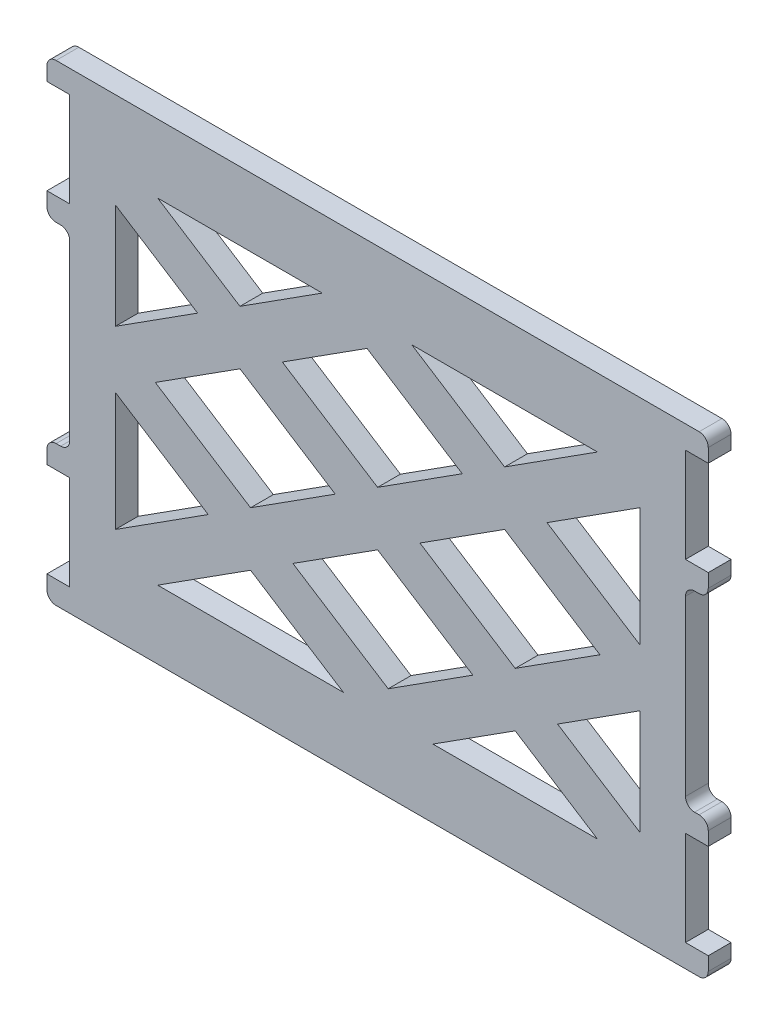
SolidWorks part; units mm, degrees
ref_plane "Front Plane" through (0, 0, 0) normal (0, 0, 1) x (1, 0, 0)
ref_plane "Top Plane" through (0, 0, 0) normal (0, 1, 0) x (1, 0, 0)
ref_plane "Right Plane" through (0, 0, 0) normal (1, 0, 0) x (0, 0, -1)
sketch "Sketch1" plane through (0, 0, 0) normal (0, 0, 1) x (1, 0, 0)
  line L1 (-44.9115, 28.3715) -> (9.0885, 28.3715)
  line L2 (-44.9115, 28.3715) -> (-44.9115, -9.0285)
  line L3 (-44.9115, -9.0285) -> (9.0885, -9.0285)
  line L4 (9.0885, 28.3715) -> (9.0885, -9.0285)
  dimension "D1" = 54
  dimension "D2" = 37.4
extrude "Boss-Extrude1" add sketch "Sketch1" along normal blind 2
sketch "Sketch2" plane through (0, 0, 2) normal (0, 0, 1) x (1, 0, 0)
  line L0 (-37.1977, 24.3715) -> (-29.9813, 19.7593)
  line L1 (-40.9115, 21.9979) -> (-33.6951, 17.3857)
  line L2 (1.3747, 24.3715) -> (-6.7702, 19.1659)
  line L3 (5.0885, 21.9979) -> (-3.0564, 16.7923)
  line L4 (-40.9115, 24.3715) -> (5.0885, -5.0285) construction
  line L5 (5.0885, 24.3715) -> (-40.9115, -5.0285) construction
  line L6 (-22.7649, 24.3715) -> (-29.9813, 19.7593)
  line L7 (-37.4089, 10.2649) -> (-18.84, 22.1329)
  line L8 (-40.9115, 24.3715) -> (-40.9115, -5.0285)
  line L9 (-40.9115, -5.0285) -> (5.0885, -5.0285)
  line L10 (5.0885, -5.0285) -> (5.0885, 24.3715)
  line L11 (5.0885, 24.3715) -> (-40.9115, 24.3715)
  line L12 (-40.9115, 21.9979) -> (-40.9115, 12.7735)
  line L13 (-37.1977, -5.0285) -> (-20.908, -5.0285)
  line L14 (5.0885, -2.6549) -> (5.0885, 6.5696)
  line L15 (1.3747, 24.3715) -> (-14.915, 24.3715)
  line L16 (-13.0581, -5.0285) -> (-5.8417, -0.4163)
  line L17 (-16.9831, -2.7898) -> (-9.5555, 1.9573)
  line L18 (-14.915, 24.3715) -> (-6.7702, 19.1659)
  line L19 (-18.84, 22.1329) -> (-10.4839, 16.7923)
  line L20 (-40.9115, 7.7564) -> (-32.7667, 2.5507)
  line L21 (-37.4089, 10.2649) -> (-29.0529, 4.9243)
  line L22 (-3.0564, 16.7923) -> (5.0885, 11.5867)
  line L23 (-6.7702, 14.4187) -> (1.5859, 9.0781)
  line L24 (-10.4839, 16.7923) -> (-17.9115, 12.0451)
  line L25 (-6.7702, 14.4187) -> (-14.1977, 9.6715)
  line L26 (-33.6951, 17.3857) -> (-40.9115, 12.7735)
  line L27 (-29.9813, 15.0121) -> (-21.6253, 9.6715)
  line L28 (-26.2675, 17.3857) -> (-17.9115, 12.0451)
  line L29 (-32.7667, 2.5507) -> (-40.9115, -2.6549)
  line L30 (-29.0529, 0.1771) -> (-37.1977, -5.0285)
  line L31 (-5.8417, 4.3309) -> (1.5859, 9.0781)
  line L32 (-2.1279, 1.9573) -> (5.0885, 6.5696)
  line L33 (-2.1279, 1.9573) -> (5.0885, -2.6549)
  line L34 (-5.8417, -0.4163) -> (1.3747, -5.0285)
  line L35 (-21.6253, 9.6715) -> (-29.0529, 4.9243)
  line L36 (-17.9115, 7.2979) -> (-9.5555, 1.9573)
  line L37 (-17.9115, 7.2979) -> (-25.3391, 2.5507)
  line L38 (-14.1977, 9.6715) -> (-5.8417, 4.3309)
  line L39 (-22.7649, 24.3715) -> (-37.1977, 24.3715)
  line L40 (5.0885, 11.5867) -> (5.0885, 21.9979)
  line L41 (-13.0581, -5.0285) -> (1.3747, -5.0285)
  line L42 (-40.9115, 7.7564) -> (-40.9115, -2.6549)
  line L43 (-25.3391, 2.5507) -> (-16.9831, -2.7898)
  line L44 (-29.0529, 0.1771) -> (-20.908, -5.0285)
  dimension "D2" = 2
  dimension "D3" = 2
  dimension "D4" = 2
  dimension "D5" = 2
  dimension "D6" = 15
  dimension "D7" = 4
  dimension "D8" = 15
  dimension "D9" = 4
  dimension "D10" = 14
  dimension "D11" = 4
  dimension "D12" = 14
  dimension "D13" = 4
  dimension "D1" = 4
extrude "Cut-Extrude1" cut sketch "Sketch2" against normal through all contours L6 L39 L0 | L26 L1 L12 | L35 L27 L7 L21 | L7 L28 L24 L19 | L15 L18 L2 | L22 L40 L3 | L25 L38 L31 L23 | L37 L43 L17 L36 | L44 L30 L13 | L20 L42 L29 | L16 L41 L34 | L32 L33 L14
ref_plane "Plane1" through (0, 9.6715, 0) normal (0, -1, 0) x (-1, 0, 0)
ref_plane "Plane2" through (-17.9115, 0, 0) normal (-1, 0, 0) x (0, 0, 1)
sketch "Sketch3" plane through (0, -9.0285, 0) normal (0, -1, 0) x (1, 0, 0)
  line L0 (9.0885, 2) -> (11.0885, 2)
  line L1 (11.0885, 2) -> (11.0885, 0)
  line L2 (11.0885, 0) -> (9.0885, 0)
  line L3 (-44.9115, 0) -> (9.0885, 0) construction
  line L4 (-44.9115, 2) -> (-46.9115, 2)
  line L5 (-46.9115, 2) -> (-46.9115, 0)
  line L6 (-46.9115, 0) -> (-44.9115, 0)
  line L7 (-44.9115, 2) -> (-44.9115, 0) construction
  line L8 (9.0885, 2) -> (9.0885, 0) construction
  line L9 (-44.9115, 2) -> (9.0885, 2)
  line L10 (9.0885, 0) -> (-44.9115, 0)
  dimension "D1" = 2
  dimension "D2" = 2
extrude "Boss-Extrude2" add sketch "Sketch3" along normal blind 2
sketch "Sketch4" plane through (9.0885, 0, 0) normal (1, 0, 0) x (0, 0, -1)
  line L0 (-2, -9.0285) -> (0, -9.0285) construction
  line L1 (-2, -0.7285) -> (0, -0.7285)
  line L2 (-2, -0.7285) -> (-2, 1.2715)
  line L3 (-2, 1.2715) -> (0, 1.2715)
  line L4 (0, -0.7285) -> (0, 1.2715)
  line L5 (-2, -9.0285) -> (-2, 28.3715) construction
  line L6 (0, -9.0285) -> (0, 28.3715) construction
  point P4 (-1, -9.0285)
  dimension "D1" = 8.3
  dimension "D2" = 2
extrude "Boss-Extrude3" add sketch "Sketch4" along normal blind 2
mirror "Mirror2" about plane through (-17.9115, 0, 0) normal (-1, 0, 0) of "Boss-Extrude3"
fillet "Fillet3" radius 0.8 6 edges at (9.0885, 1.2715, 1) (11.0885, 1.2715, 1) (-46.9115, 1.2715, 1) (-44.9115, 1.2715, 1) (-46.9115, -11.0285, 1) (11.0885, -11.0285, 1)
mirror "Mirror5" about plane through (0, 9.6715, 0) normal (0, -1, 0) of "Boss-Extrude2", "Boss-Extrude3", "Mirror2", "Fillet3"
